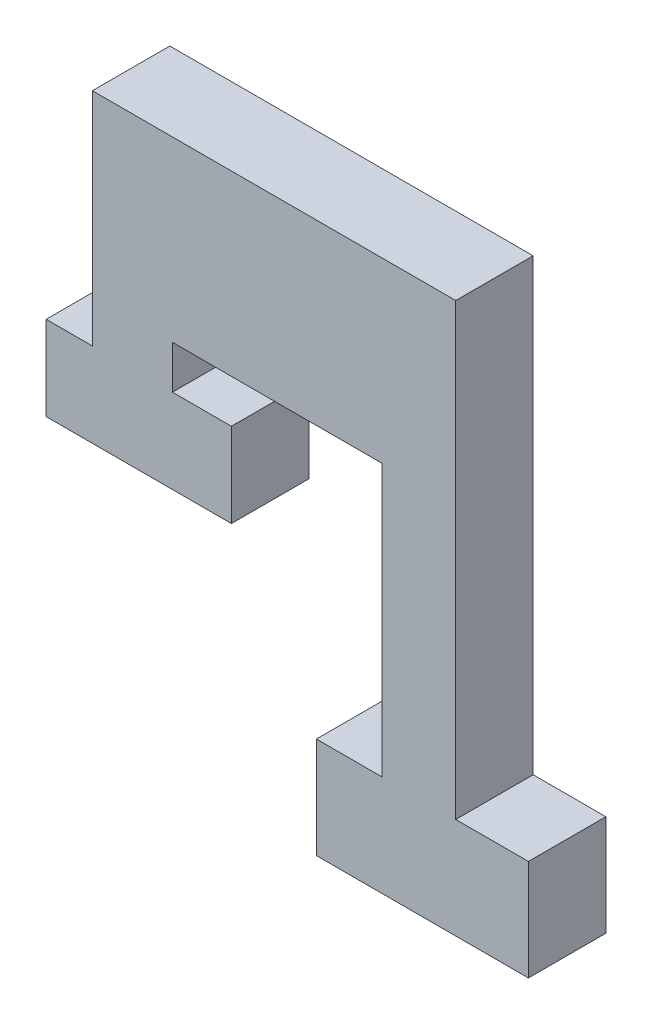
SolidWorks part; units mm, degrees
ref_plane "Front Plane" through (0, 0, 0) normal (0, 0, 1) x (1, 0, 0)
ref_plane "Top Plane" through (0, 0, 0) normal (0, 1, 0) x (1, 0, 0)
ref_plane "Right Plane" through (0, 0, 0) normal (1, 0, 0) x (0, 0, -1)
sketch "Sketch1" plane through (0, 0, 0) normal (0, 0, 1) x (1, 0, 0)
  line L0 (-57.8583, 0) -> (-57.8583, 45.9362)
  line L1 (-57.8583, 45.9362) -> (35.9827, 45.9362)
  line L2 (35.9827, 45.9362) -> (35.9827, -85.9663)
  line L3 (35.9827, -85.9663) -> (16.952, -85.9663)
  line L4 (16.952, -85.9663) -> (16.952, 0)
  line L5 (16.952, 0) -> (-37.187, 0)
  line L6 (-37.187, 0) -> (-37.187, -22.64)
  line L7 (-37.187, -22.64) -> (-57.8583, -22.64)
  line L8 (-57.8583, -22.64) -> (-57.8583, 0)
extrude "Boss-Extrude1" add sketch "Sketch1" along normal blind 20
sketch "Sketch3" plane through (0, 0, 0) normal (0, 0, 1) x (1, 0, 0)
  line L1 (-69.7905, -11.1555) -> (-21.9489, -11.1555)
  line L2 (-69.7905, -11.1555) -> (-69.7905, -32.9247)
  line L3 (-69.7905, -32.9247) -> (-21.9489, -32.9247)
  line L4 (-21.9489, -11.1555) -> (-21.9489, -32.9247)
  line L5 (0, -70.1348) -> (54.7495, -70.1348)
  line L6 (0, -70.1348) -> (0, -96.2072)
  line L7 (0, -96.2072) -> (54.7495, -96.2072)
  line L8 (54.7495, -70.1348) -> (54.7495, -96.2072)
extrude "Boss-Extrude2" add sketch "Sketch3" along normal blind 20
